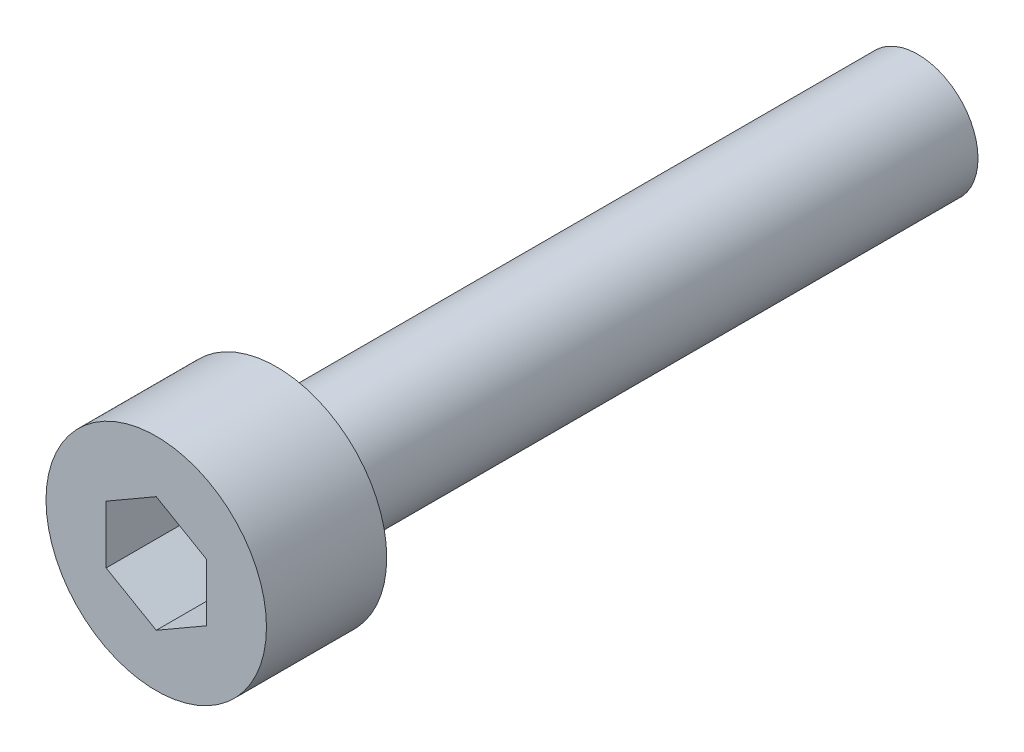
SolidWorks part; units mm, degrees
ref_plane "前视基准面" through (0, 0, 0) normal (0, 0, 1) x (1, 0, 0)
ref_plane "上视基准面" through (0, 0, 0) normal (0, 1, 0) x (1, 0, 0)
ref_plane "右视基准面" through (0, 0, 0) normal (1, 0, 0) x (0, 0, -1)
other "Configuration Table"
sketch "Profile_1" plane through (0, 0, 0) normal (0, 0, 1) x (1, 0, 0)
  circle A0 centre (0, 0) radius 1.5
extrude "Thread_envelope" add sketch "Profile_1" along normal blind 16 from offset 16
sketch "Profile_2" plane through (0, 0, 0) normal (0, 0, 1) x (1, 0, 0)
  line L0 (1.25, 0.7217) -> (0, 1.4434)
  line L1 (0, 1.4434) -> (-1.25, 0.7217)
  line L2 (-1.25, 0.7217) -> (-1.25, -0.7217)
  line L3 (-1.25, -0.7217) -> (0, -1.4434)
  line L4 (0, -1.4434) -> (1.25, -0.7217)
  line L5 (1.25, -0.7217) -> (1.25, 0.7217)
  circle A0 centre (0, 0) radius 2.75
extrude "Socket_head" add sketch "Profile_2" along normal blind 3 from offset 0
